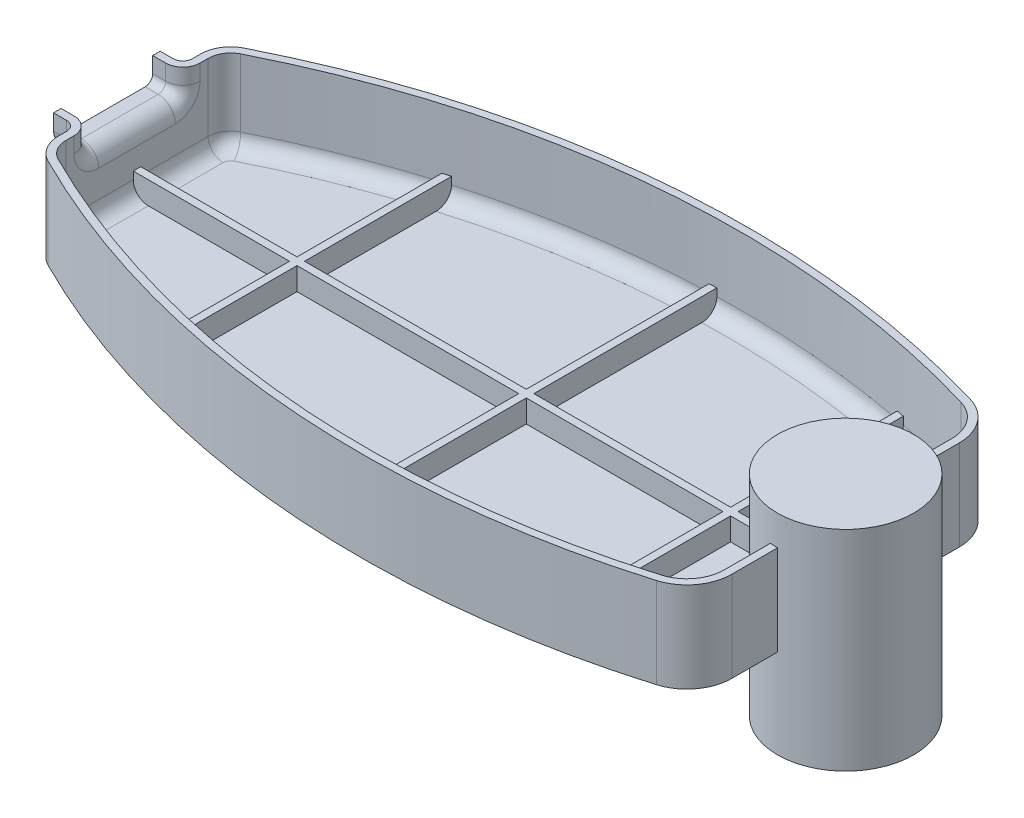
SolidWorks part; units mm, degrees
ref_plane "Front Plane" through (0, 0, 0) normal (0, 0, 1) x (1, 0, 0)
ref_plane "Top Plane" through (0, 0, 0) normal (0, 1, 0) x (1, 0, 0)
ref_plane "Right Plane" through (0, 0, 0) normal (1, 0, 0) x (0, 0, -1)
sketch "Sketch1" plane through (0, 0, 0) normal (0, 1, 0) x (1, 0, 0)
  line L0 (0, 0) -> (144.4846, 0) construction
  line L1 (151.1466, 23.9986) -> (151.1466, -23.9986)
  line L2 (151.1466, -30.9662) -> (151.3934, -31.9532)
  line L3 (0, 15.0032) -> (0, -15.0032)
  line L4 (0, -18.8758) -> (0.3867, -17.8889)
  arc A0 (3.5015, 20.6785) -> (144.3346, 33.1291) centre (89.6407, -150.9401) cw
  arc A1 (3.5015, -20.6785) -> (144.3346, -33.1291) centre (89.6407, 150.9401) ccw
  arc A2 (3.5015, -20.6785) -> (0, -15.0032) centre (6.35, -15.0032) cw
  arc A3 (3.5015, 20.6785) -> (0, 15.0032) centre (6.35, 15.0032) ccw
  arc A4 (144.3346, -33.1291) -> (151.1466, -23.9986) centre (141.6216, -23.9986) ccw
  arc A5 (144.3346, 33.1291) -> (151.1466, 23.9986) centre (141.6216, 23.9986) cw
  point P16 (0, 18.8758)
  point P22 (151.1466, 30.9662)
  dimension "D1" = 6.35
  dimension "D2" = 9.525
extrude "Boss-Extrude1" add sketch "Sketch1" against normal blind 19.05
ref_plane "Plane1" through (-4.7752, 0, 0) normal (-1, 0, 0) x (0, 0, 1)
sketch "Sketch2" plane through (-4.7752, 0, 0) normal (-1, 0, 0) x (0, 0, 1)
  line L0 (0, 0) -> (0, -2.8991) construction
  line L1 (0, 0) -> (11.256, 0)
  line L2 (-15.0032, 0) -> (15.0032, 0) construction
  line L3 (-11.256, 0) -> (-11.256, -3.3329)
  line L4 (-8.081, -6.5079) -> (8.081, -6.5079)
  line L5 (11.256, 0) -> (11.256, -3.3329)
  line L8 (0, 0) -> (-11.256, 0)
  arc A0 (-11.256, -3.3329) -> (-8.081, -6.5079) centre (-8.081, -3.3329) ccw
  arc A1 (8.081, -6.5079) -> (11.256, -3.3329) centre (8.081, -3.3329) ccw
  dimension "D1" = 3.175
extrude "Boss-Extrude2" add sketch "Sketch2" against normal up to body
fillet "Fillet2" radius 2.032 5 edges at (0, -1.6664, -11.256) (0, -5.5779, -10.3261) (0, -6.5079, 0) (0, -5.5779, 10.3261) (0, -1.6664, 11.256)
shell "Shell1" thickness 1.5875
ref_plane "Plane2" through (0, -12.7, 0) normal (0, 1, 0) x (-1, 0, 0)
sketch "Sketch3" plane through (0, -12.7, 0) normal (0, 1, 0) x (-1, 0, 0)
  line L0 (-3.175, 0) -> (-147.9716, 0)
  line L3 (-35.354, 29.9372) -> (-35.354, 6.3672)
  line L4 (-35.354, -3.6768) -> (-35.354, -21.6126)
  line L5 (-83.7435, 37.816) -> (-83.7435, 6.3672)
  line L6 (-83.7435, -3.6768) -> (-83.7435, -26.9933)
  line L7 (-126.8635, 34.2033) -> (-126.8635, 3.8562)
  line L8 (-126.8635, -3.6768) -> (-126.8635, -24.1236)
  line L9 (-83.7435, 6.3672) -> (-83.7435, -3.6768) construction
  point P21 (-83.7435, 0)
ref_plane "Plane3" through (0, -25.4, 0) normal (0, 1, 0) x (-1, 0, 0)
sketch "Sketch4" plane through (0, -25.4, 0) normal (0, 1, 0) x (-1, 0, 0)
  point P0 (-83.7435, 0)
ref_plane "Plane4" through (0, 6.35, 0) normal (0, 1, 0) x (-1, 0, 0)
sketch "Sketch6" plane through (0, 6.35, 0) normal (0, 1, 0) x (-1, 0, 0)
  line L0 (-151.1466, -23.9986) -> (-151.1466, 23.9986) construction
  circle A0 centre (-151.1466, 0) radius 14.3855
extrude "Boss-Extrude3" add sketch "Sketch6" against normal blind 44.196 separate body
fillet "Fillet3" radius 3.175 8 edges at (2.2969, -17.4625, 17.5039) (1.5875, -17.4625, 0) (2.2969, -17.4625, -17.5039) (72.8703, -17.4625, -38.7557) (147.9836, -17.4625, -28.7451) (149.5591, -17.4625, 0) (147.9836, -17.4625, 28.7451) (72.8703, -17.4625, 38.7557)
rib "Rib1" sketch "Sketch3" sketch "Sketch3" thickness 1.5875 extrusion direction normal to sketch draft on no parameters "D1"=1.5875
